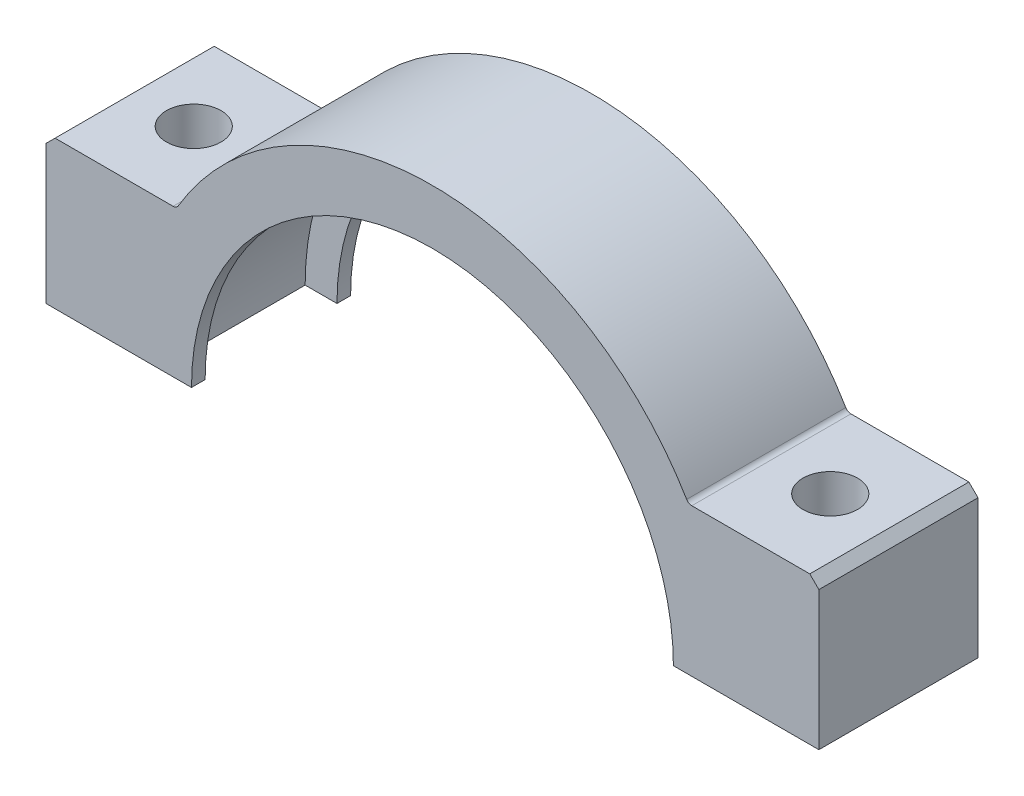
SolidWorks part; units mm, degrees
ref_plane "Płaszczyzna przednia" through (0, 0, 0) normal (0, 0, 1) x (1, 0, 0)
ref_plane "Płaszczyzna górna" through (0, 0, 0) normal (0, 1, 0) x (1, 0, 0)
ref_plane "Płaszczyzna prawa" through (0, 0, 0) normal (1, 0, 0) x (0, 0, -1)
sketch "Szkic1" plane through (0, 0, 0) normal (0, 0, 1) x (1, 0, 0)
  line L0 (-85, 30.5) -> (-83, 32.5)
  line L1 (-60, 0) -> (-85, 0)
  line L2 (60, 0) -> (85, 0)
  line L4 (-85, 0) -> (-85, 30.5)
  line L5 (83, 32.5) -> (85, 30.5)
  line L7 (85, 30.5) -> (85, 0)
  line L8 (-83, 32.5) -> (-57.0464, 32.5)
  line L10 (57.0464, 32.5) -> (83, 32.5)
  arc A0 (60, 0) -> (-60, 0) centre (0, 0) ccw
  arc A1 (55.9143, 33.1449) -> (-55.9143, 33.1449) centre (0, 0) ccw
  arc A2 (57.0464, 32.5) -> (55.9143, 33.1449) centre (57.0464, 33.816) cw
  arc A3 (-57.0464, 32.5) -> (-55.9143, 33.1449) centre (-57.0464, 33.816) ccw
  point P11 (-85, 32.5)
  point P14 (85, 32.5)
  dimension "D1" = 120
  dimension "D5" = 1.316
  dimension "D2" = 25
  dimension "D3" = 25
extrude "Dodanie-wyciągnięcie1" add sketch "Szkic1" along normal mid plane 29 contours L8 A3 A1 A2 L10 L5 L7 L2 A0 L1 L4 L0
hole_wizard "Otwór Ø12.0 (12)1" positions "Szkic3" profile "Szkic2" hole size "Ø12.0" standard "DIN" end condition up to next
sketch "Szkic3" plane through (0, 0, 0) normal (0, -1, 0) x (-1, 0, 0)
  line L0 (85, -14.5) -> (85, 14.5) construction
  line L1 (-85, -14.5) -> (-85, 14.5) construction
  point P0 (70, 0)
  point P5 (-70, 0)
  dimension "D1" = 15
  dimension "D2" = 15
sketch "Szkic2" plane through (-70, 0, 0) normal (1, 0, 0) x (0, 0, -1)
  line L0 (0, 0) -> (0, 32.5)
  line L1 (0, 32.5) -> (6, 32.5)
  line L2 (6, 32.5) -> (6, 0)
  line L5 (6, 0) -> (0, 0)
  line L11 (0, -6.35) -> (0, 107.95) construction
  dimension "Średnica otworu na wylot" = 12
  dimension "Głębokość otworu na wylot" = 32.5
sketch "Szkic4" plane through (0, 0, -14.5) normal (0, 0, -1) x (-1, 0, 0)
  line L0 (-53, 0) -> (-85, 0)
  line L1 (-85, 0) -> (-85, 30.5)
  line L2 (-85, 30.5) -> (-83, 32.5)
  line L3 (-83, 32.5) -> (-57.0464, 32.5)
  line L4 (53, 0) -> (85, 0)
  line L5 (85, 0) -> (85, 30.5)
  line L6 (85, 30.5) -> (83, 32.5)
  line L7 (83, 32.5) -> (57.0464, 32.5)
  arc A0 (53, 0) -> (-53, 0) centre (0, 0) ccw
  arc A1 (-57.0464, 32.5) -> (-55.9143, 33.1449) centre (-57.0464, 33.816) ccw
  arc A2 (57.0464, 32.5) -> (55.9143, 33.1449) centre (57.0464, 33.816) cw
  arc A3 (-55.9143, 33.1449) -> (55.9143, 33.1449) centre (0, 0) cw
  dimension "D1" = 106
extrude "Dodanie-wyciągnięcie2" add sketch "Szkic4" along normal blind 3
sketch "Szkic5" plane through (0, 0, 14.5) normal (0, 0, 1) x (1, 0, 0)
  line L0 (-53, 0) -> (-85, 0)
  line L1 (-85, 0) -> (-85, 30.5)
  line L2 (-85, 30.5) -> (-83, 32.5)
  line L3 (-83, 32.5) -> (-57.0464, 32.5)
  line L4 (53, 0) -> (85, 0)
  line L5 (85, 0) -> (85, 30.5)
  line L6 (85, 30.5) -> (83, 32.5)
  line L7 (83, 32.5) -> (57.0464, 32.5)
  arc A0 (53, 0) -> (-53, 0) centre (0, 0) ccw
  arc A1 (-57.0464, 32.5) -> (-55.9143, 33.1449) centre (-57.0464, 33.816) ccw
  arc A2 (57.0464, 32.5) -> (55.9143, 33.1449) centre (57.0464, 33.816) cw
  arc A3 (-55.9143, 33.1449) -> (55.9143, 33.1449) centre (0, 0) cw
  dimension "D1" = 106
extrude "Dodanie-wyciągnięcie3" add sketch "Szkic5" along normal blind 3
